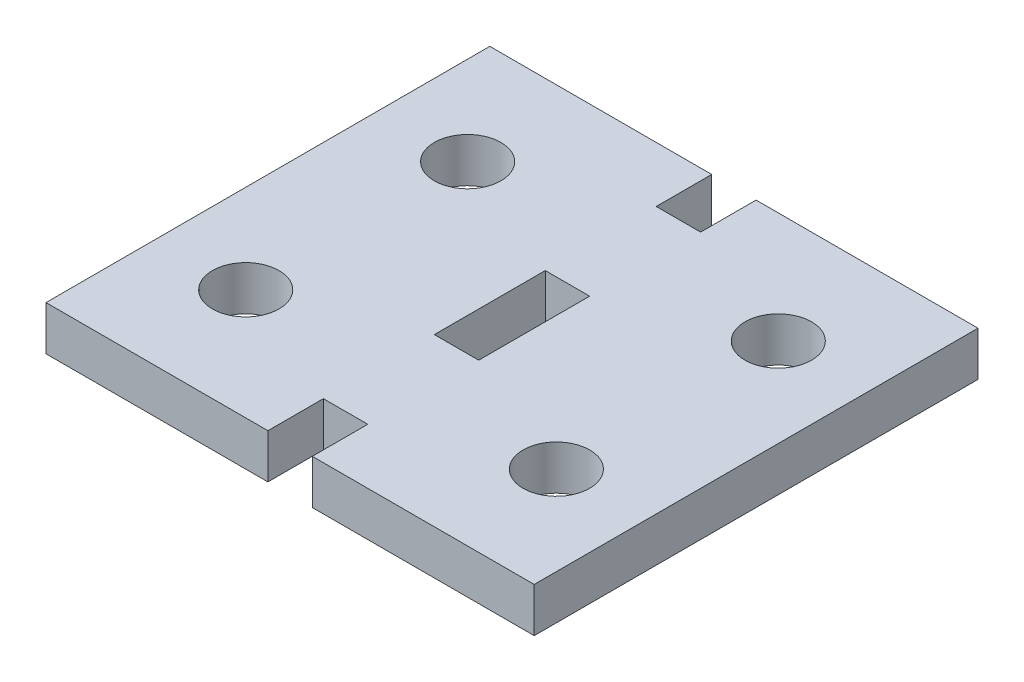
SolidWorks part; units mm, degrees
ref_plane "Front Plane" through (0, 0, 0) normal (0, 0, 1) x (1, 0, 0)
ref_plane "Top Plane" through (0, 0, 0) normal (0, 1, 0) x (1, 0, 0)
ref_plane "Right Plane" through (0, 0, 0) normal (1, 0, 0) x (0, 0, -1)
sketch "Sketch1" plane through (0, 0, 0) normal (0, 1, 0) x (1, 0, 0)
  line L1 (-11, 10) -> (11, 10)
  line L2 (-11, 10) -> (-11, -10)
  line L3 (-11, -10) -> (11, -10)
  line L4 (11, 10) -> (11, -10)
  line L5 (-11, 10) -> (11, -10) construction
  line L6 (-11, -10) -> (11, 10) construction
  point P0 (0, 0)
  dimension "D1" = 22
  dimension "D2" = 20
extrude "Boss-Extrude1" add sketch "Sketch1" along normal blind 2
sketch "Sketch2" plane through (0, 2, 0) normal (0, 1, 0) x (1, 0, 0)
  line L0 (0, 11.8612) -> (0, 7.5) construction
  line L1 (11, 10) -> (-11, 10) construction
  line L2 (-1, 7.5) -> (1, 7.5)
  line L4 (-1, 2.5) -> (1, 2.5)
  line L8 (-1, -2.5) -> (1, -2.5)
  line L9 (0, 2.5) -> (0, -2.5) construction
  line L10 (-1, -7.5) -> (1, -7.5)
  line L14 (-11, -10) -> (11, -10) construction
  line L17 (-7, 11.4406) -> (-7, -15.1988) construction
  line L18 (7, 11.8612) -> (7, -15.1988) construction
  line L19 (-11, 10) -> (-11, -10) construction
  line L20 (11, -10) -> (11, 10) construction
  line L21 (-1, 7.5) -> (-1, 10)
  line L22 (-1, 10) -> (1, 10)
  line L23 (1, 10) -> (1, 7.5)
  line L24 (-1, -7.5) -> (-1, -10)
  line L25 (-1, -10) -> (1, -10)
  line L26 (1, -10) -> (1, -7.5)
  line L27 (-1, 2.5) -> (-1, -2.5)
  line L28 (1, 2.5) -> (1, -2.5)
  line L29 (0, -7.5) -> (0, -12.8319) construction
  circle A0 centre (-7, 5) radius 1.5
  circle A1 centre (-7, -5) radius 1.5
  circle A2 centre (7, 5) radius 1.5
  circle A3 centre (7, -5) radius 1.5
  point P3 (0, 5)
  point P8 (0, -5)
  dimension "D9" = 3
  dimension "D10" = 5
  dimension "D1" = 2
  dimension "D2" = 2
  dimension "D3" = 5
  dimension "D4" = 5
  dimension "D5" = 5
  dimension "D6" = 5
  dimension "D7" = 4
  dimension "D8" = 4
  dimension "D11" = 5
  dimension "D12" = 5
  dimension "D13" = 5
extrude "Cut-Extrude1" cut sketch "Sketch2" against normal blind 2
